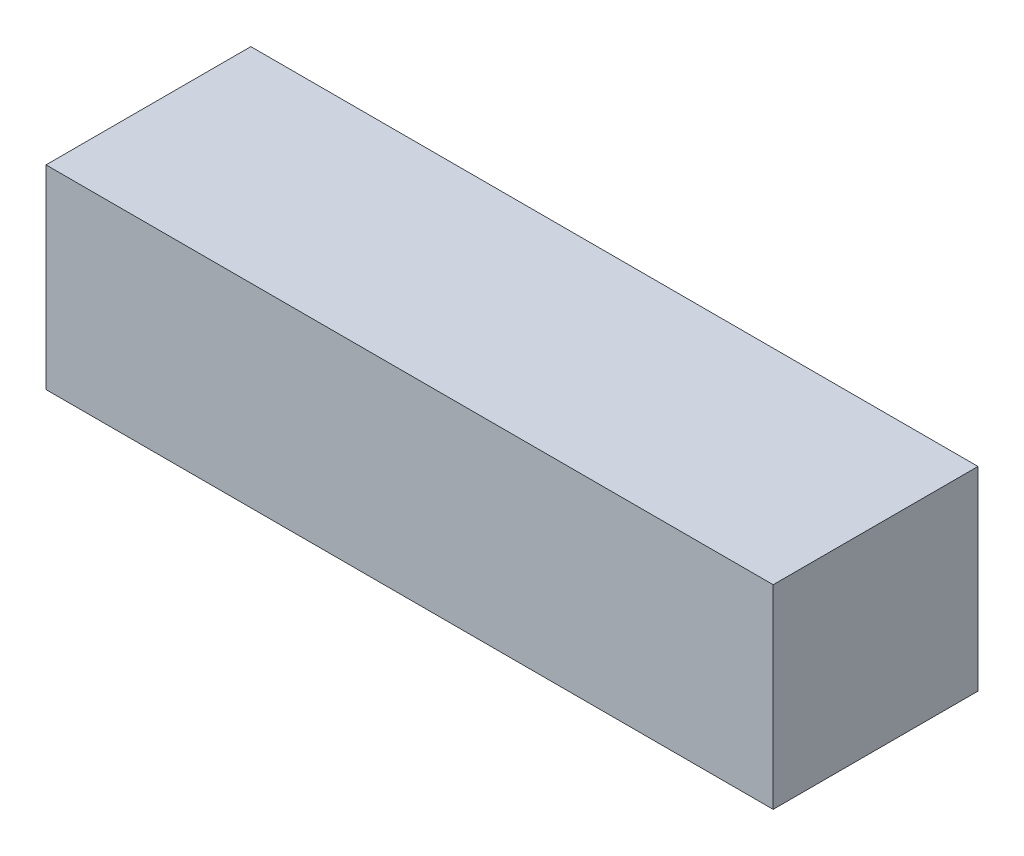
SolidWorks part; units mm, degrees
ref_plane "前视基准面" through (0, 0, 0) normal (0, 0, 1) x (1, 0, 0)
ref_plane "上视基准面" through (0, 0, 0) normal (0, 1, 0) x (1, 0, 0)
ref_plane "右视基准面" through (0, 0, 0) normal (1, 0, 0) x (0, 0, -1)
sketch "草图1" plane through (0, 0, 0) normal (0, 1, 0) x (1, 0, 0)
  line L1 (-71, 20) -> (71, 20)
  line L2 (-71, 20) -> (-71, -20)
  line L3 (-71, -20) -> (71, -20)
  line L4 (71, 20) -> (71, -20)
  line L5 (-71, 20) -> (71, -20) construction
  line L6 (-71, -20) -> (71, 20) construction
  point P0 (0, 0)
  dimension "D1" = 142
  dimension "D2" = 40
extrude "凸台-拉伸1" add sketch "草图1" along normal blind 38
